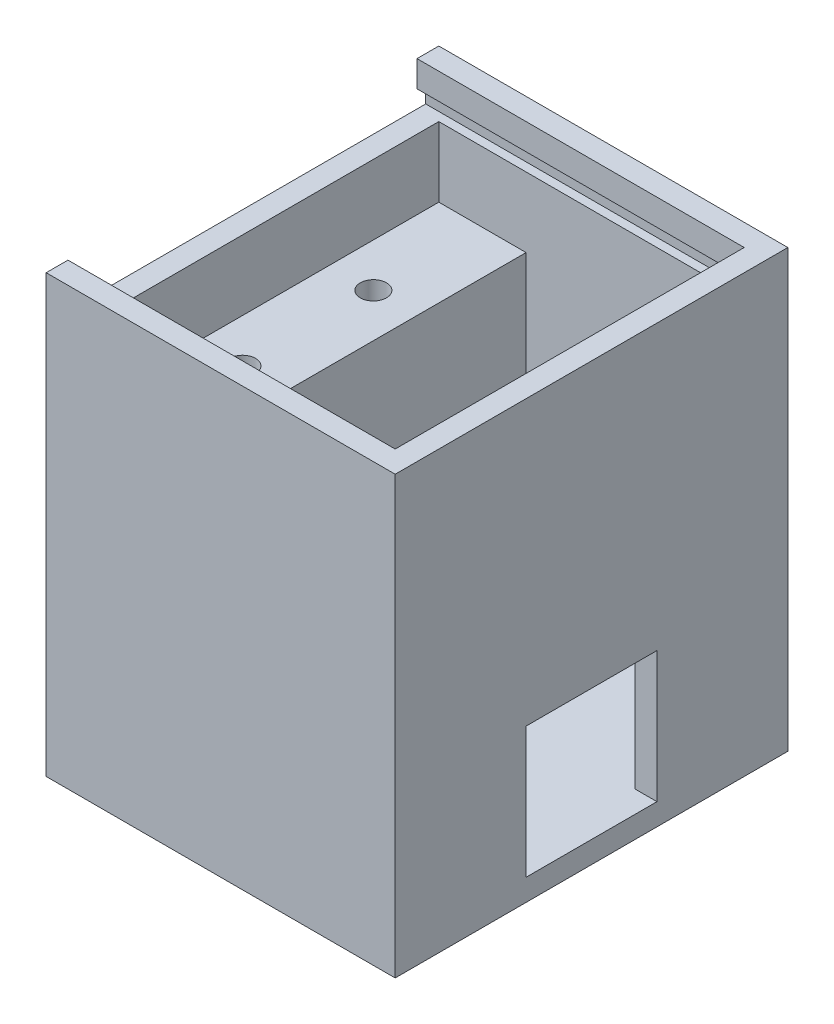
SolidWorks part; units mm, degrees
ref_plane "Front Plane" through (0, 0, 0) normal (0, 0, 1) x (1, 0, 0)
ref_plane "Top Plane" through (0, 0, 0) normal (0, 1, 0) x (1, 0, 0)
ref_plane "Right Plane" through (0, 0, 0) normal (1, 0, 0) x (0, 0, -1)
sketch "Sketch1" plane through (0, 0, 0) normal (0, 1, 0) x (1, 0, 0)
  line L1 (-34.8887, 14.0503) -> (5.1113, 14.0503)
  line L2 (-34.8887, 14.0503) -> (-34.8887, -30.9497)
  line L3 (-34.8887, -30.9497) -> (5.1113, -30.9497)
  line L4 (5.1113, 14.0503) -> (5.1113, -30.9497)
extrude "Boss-Extrude1" add sketch "Sketch1" along normal blind 50
shell "Shell1" thickness 2.5
sketch "Sketch3" plane through (-32.3887, 0, 0) normal (1, 0, 0) x (0, 0, -1)
  line L0 (-28.4497, 50) -> (-28.4497, 2.5) construction
  line L1 (11.5503, 2.5) -> (-28.4497, 2.5)
  line L2 (11.5503, 2.5) -> (11.5503, 37)
  line L3 (11.5503, 37) -> (-28.4497, 37)
  line L4 (-28.4497, 2.5) -> (-28.4497, 37)
extrude "Boss-Extrude2" add sketch "Sketch3" along normal blind 10
sketch "Sketch11" plane through (-32.3887, 0, 0) normal (1, 0, 0) x (0, 0, -1)
  line L0 (-28.4497, 50) -> (-28.4497, 37) construction
  line L1 (11.5503, 50) -> (-28.4497, 50)
  line L2 (11.5503, 50) -> (11.5503, 45)
  line L3 (11.5503, 45) -> (-28.4497, 45)
  line L4 (-28.4497, 50) -> (-28.4497, 45)
extrude "Cut-Extrude2" cut sketch "Sketch11" against normal blind 2.5
sketch "Sketch12" plane through (0, 0, -11.5503) normal (0, 0, 1) x (1, 0, 0)
  line L0 (2.6113, 50) -> (2.6113, 2.5) construction
  line L1 (-34.8887, 45) -> (2.6113, 45)
  line L2 (-34.8887, 45) -> (-34.8887, 47)
  line L3 (-34.8887, 47) -> (2.6113, 47)
  line L4 (2.6113, 45) -> (2.6113, 47)
sketch "Sketch13" plane through (0, 0, 28.4497) normal (0, 0, -1) x (-1, 0, 0)
  line L0 (-2.6113, 50) -> (-2.6113, 2.5) construction
  line L1 (34.8887, 45) -> (-2.6113, 45)
  line L2 (34.8887, 45) -> (34.8887, 47)
  line L3 (34.8887, 47) -> (-2.6113, 47)
  line L4 (-2.6113, 45) -> (-2.6113, 47)
extrude "Cut-Extrude3" cut sketch "Sketch12" against normal blind 1
extrude "Cut-Extrude4" cut sketch "Sketch13" against normal blind 1
sketch "Sketch14" plane through (0, 37, 0) normal (0, 1, 0) x (1, 0, 0)
  line L0 (-32.3887, -28.4497) -> (-22.3887, 11.5503)
  line L1 (-22.3887, -28.4497) -> (-32.3887, 11.5503)
  line L2 (-27.3887, -28.4497) -> (-27.3887, 11.5503)
  line L3 (-22.3887, -28.4497) -> (-32.3887, -28.4497) construction
  line L4 (-22.3887, 11.5503) -> (-32.3887, 11.5503) construction
  circle A0 centre (-27.3887, -8.4497) radius 7.5
  point P16 (-27.3887, -15.9497)
  point P17 (-27.3887, -0.9497)
sketch "Sketch15" plane through (0, 37, 0) normal (0, 1, 0) x (1, 0, 0)
  circle A0 centre (-27.3887, -15.9497) radius 1.5
sketch "Sketch16" plane through (0, 37, 0) normal (0, 1, 0) x (1, 0, 0)
  circle A0 centre (-27.3887, -0.9497) radius 1.5
extrude "Cut-Extrude7" cut sketch "Sketch15" against normal blind 37
extrude "Cut-Extrude8" cut sketch "Sketch16" against normal blind 37
sketch "Sketch17" plane through (0, 0, 0) normal (0, -1, 0) x (1, 0, 0)
  circle A0 centre (-27.3887, 15.9497) radius 3
  circle A1 centre (-27.3887, 0.9497) radius 3
extrude "Cut-Extrude9" cut sketch "Sketch17" against normal blind 5
sketch "Sketch18" plane through (2.6113, 0, 0) normal (-1, 0, 0) x (0, 0, 1)
  line L0 (28.4497, 2.5) -> (-11.5503, 2.5)
  circle A1 centre (8.4497, 2.5) radius 7.5
  point P4 (8.4497, 2.5)
  point P7 (15.9497, 2.5)
  point P8 (0.9497, 2.5)
  point P9 (14.3782, -129.1627)
sketch "Sketch19" plane through (2.6113, 0, 0) normal (-1, 0, 0) x (0, 0, 1)
  line L1 (15.9497, 2.5) -> (0.9497, 2.5)
  line L2 (15.9497, 2.5) -> (15.9497, 17.5)
  line L3 (15.9497, 17.5) -> (0.9497, 17.5)
  line L4 (0.9497, 2.5) -> (0.9497, 17.5)
extrude "Cut-Extrude10" cut sketch "Sketch19" against normal blind 2.5
